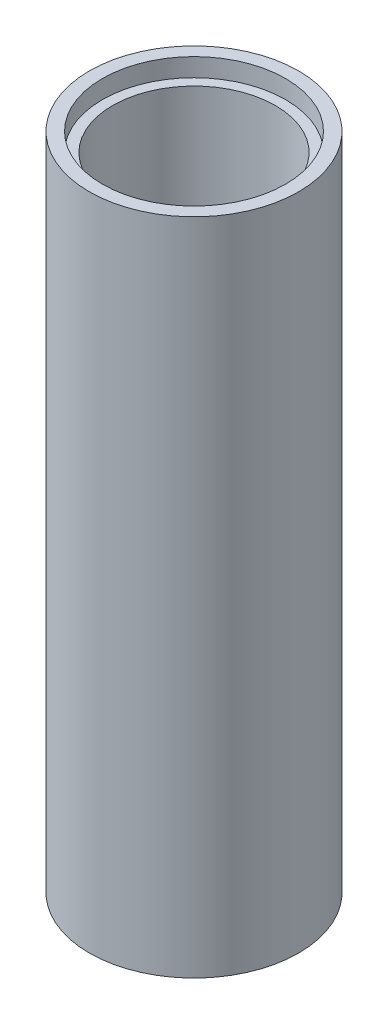
SolidWorks part; units mm, degrees
ref_plane "Front Plane" through (0, 0, 0) normal (0, 0, 1) x (1, 0, 0)
ref_plane "Top Plane" through (0, 0, 0) normal (0, 1, 0) x (1, 0, 0)
ref_plane "Right Plane" through (0, 0, 0) normal (1, 0, 0) x (0, 0, -1)
sketch "Sketch1" plane through (0, 0, 0) normal (0, 1, 0) x (1, 0, 0)
  circle A0 centre (0, 0) radius 57.15
  circle A1 centre (0, 0) radius 44.45
  dimension "D1" = 88.9
  dimension "D2" = 114.3
extrude "Boss-Extrude1" add sketch "Sketch1" along normal blind 360
sketch "Sketch2" plane through (0, 360, 0) normal (0, 1, 0) x (1, 0, 0)
  circle A0 centre (0, 0) radius 50
  dimension "D1" = 100
extrude "Cut-Extrude1" cut sketch "Sketch2" against normal blind 10
